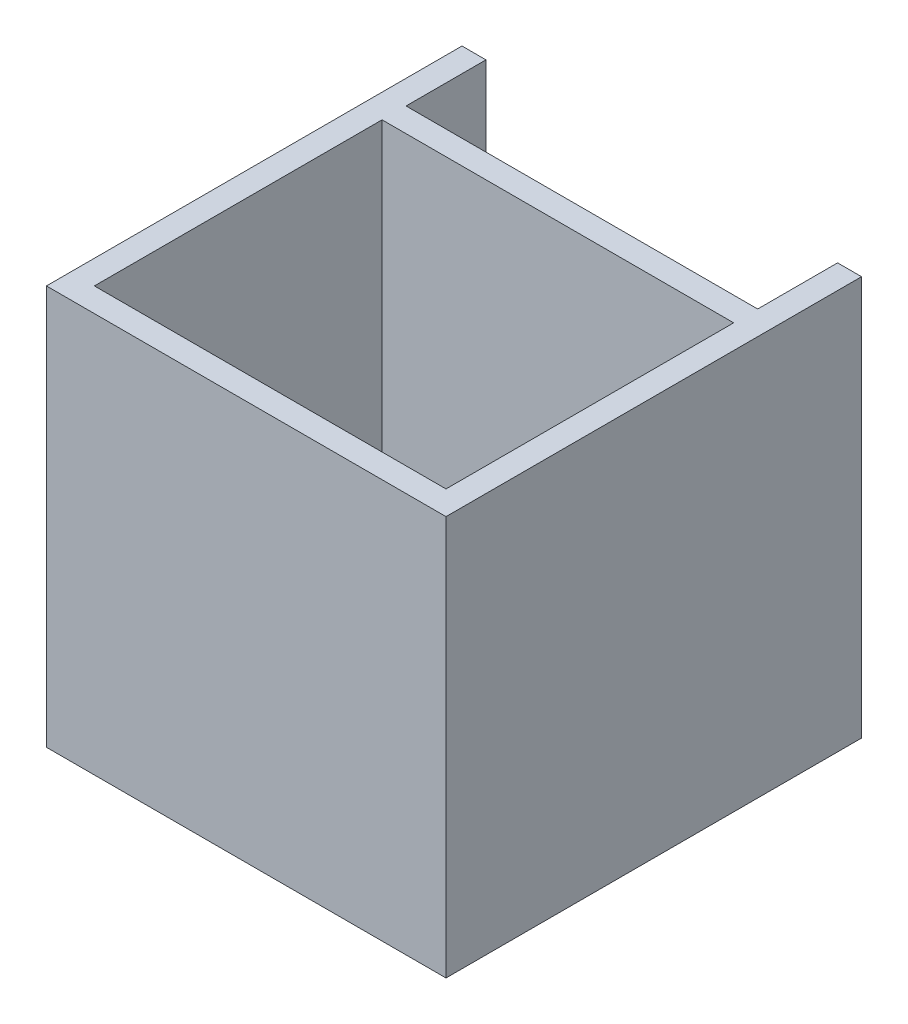
SolidWorks part; units mm, degrees
ref_plane "Спереди" through (0, 0, 0) normal (0, 0, 1) x (1, 0, 0)
ref_plane "Сверху" through (0, 0, 0) normal (0, 1, 0) x (1, 0, 0)
ref_plane "Справа" through (0, 0, 0) normal (1, 0, 0) x (0, 0, -1)
sketch "Эскиз1" plane through (0, 0, 0) normal (0, 1, 0) x (1, 0, 0)
  line L0 (-11, 8) -> (11, 8)
  line L1 (12.5, -13) -> (-12.5, -13)
  line L2 (12.5, -13) -> (12.5, 13)
  line L3 (12.5, 13) -> (11, 13)
  line L4 (-12.5, -13) -> (-12.5, 13)
  line L5 (12.5, -13) -> (-12.5, 13) construction
  line L6 (12.5, 13) -> (-12.5, -13) construction
  line L7 (12.5, 8) -> (12.5, 6)
  line L8 (-11.0577, -11.5) -> (11.0577, -11.5)
  line L9 (-12.5, 6) -> (-12.5, -11)
  line L10 (-20.5, -13) -> (20.5, -13)
  line L11 (-11, 13) -> (-12.5, 13)
  line L12 (11, -13) -> (-11, -13)
  line L13 (11, -11) -> (11, 6)
  line L14 (-11, 8) -> (-11, 13)
  line L15 (-11, -11) -> (-11, 6)
  line L16 (11, -13) -> (-11, 13) construction
  line L17 (11, 13) -> (-11, -13) construction
  line L18 (11, 8) -> (11, 13)
  line L19 (-11, 6.5) -> (12.5, 6.5)
  line L20 (-11, 6) -> (-11, 6.5)
  line L21 (11, 6.5) -> (11, 6)
  line L22 (-11, -11.5) -> (-11, -11)
  line L23 (11, -11) -> (11, -11.5)
  line L24 (-12.5, -11.5) -> (-20.5, -11.5)
  line L25 (20.5, -13) -> (20.5, -11.5)
  line L26 (20.5, -11.5) -> (12.5, -11.5)
  line L27 (-20.5, -13) -> (-20.5, -11.5)
  line L28 (0, -13) -> (-20.5, -11.5) construction
  line L29 (20.5, -11.5) -> (0, -13) construction
  line L30 (11.0577, -11.5) -> (-11.0577, -11.5)
  point P0 (0, 0)
  point P6 (-12.5, -11)
  point P7 (-12.5, 6)
  point P8 (-12.5, 8)
  point P14 (0, 0)
  point P26 (-12.5, 6.5)
  point P27 (-8.695, -11.5)
  point P31 (0, -13)
  dimension "D1" = 25
  dimension "D2" = 26
  dimension "D3" = 2
  dimension "D4" = 19
  dimension "D5" = 2
  dimension "D6" = 22
  dimension "D7" = 0.5
  dimension "D8" = 41
extrude "Бобышка-Вытянуть1" add sketch "Эскиз1" along normal blind 25
